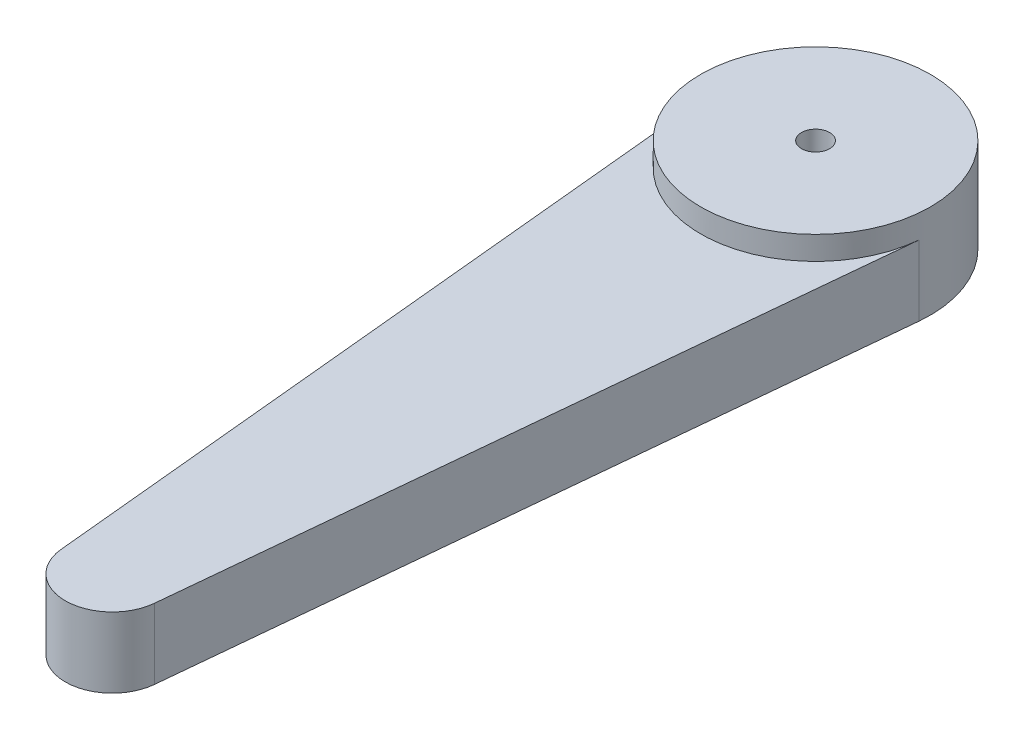
SolidWorks part; units mm, degrees
ref_plane "Alzado" through (0, 0, 0) normal (0, 0, 1) x (1, 0, 0)
ref_plane "Planta" through (0, 0, 0) normal (0, 1, 0) x (1, 0, 0)
ref_plane "Vista lateral" through (0, 0, 0) normal (1, 0, 0) x (0, 0, -1)
sketch "Croquis1" plane through (0, 0, 0) normal (0, 1, 0) x (1, 0, 0)
  circle A0 centre (0, 0) radius 3
  circle A1 centre (0, 0) radius 24.5
  dimension "D1" = 6
  dimension "D2" = 49
extrude "Saliente-Extruir1" add sketch "Croquis1" along normal blind 20
sketch "Croquis3" plane through (0, 0, 0) normal (0, -1, 0) x (1, 0, 0)
  line L0 (0, 0) -> (0, 150) construction
  line L1 (-24.6153, 0) -> (-9.9532, 150.9667)
  line L2 (24.6153, 0) -> (9.9532, 150.9667)
  arc A0 (-24.1552, 4.7367) -> (-24.6153, 0) centre (0, 0) ccw
  arc A1 (-9.9532, 150.9667) -> (9.9532, 150.9667) centre (0, 150) cw
  arc A2 (24.6153, 0) -> (24.1552, 4.7367) centre (0, 0) ccw
  circle A3 centre (0, 0) radius 24.5 construction
  dimension "D2" = 10
  dimension "D1" = 150
extrude "Saliente-Extruir2" add sketch "Croquis3" against normal blind 15
